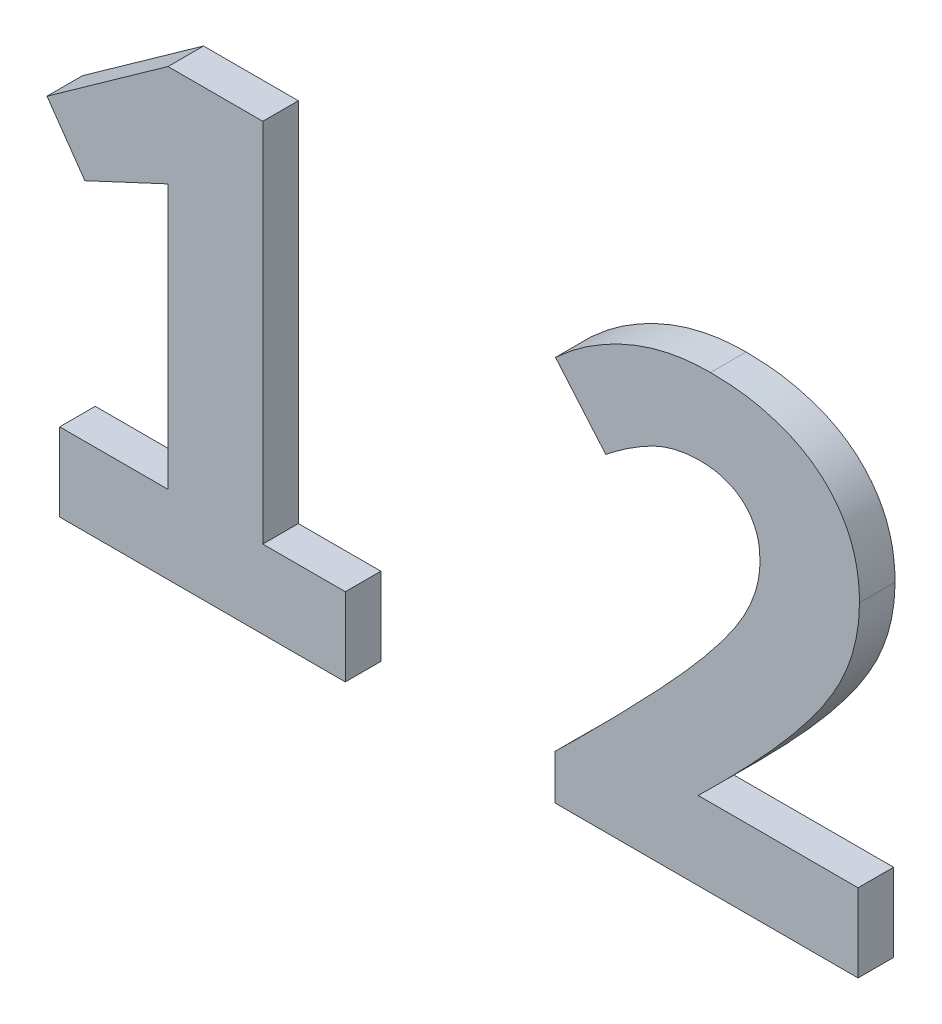
SolidWorks part; units mm, degrees
ref_plane "Front Plane" through (0, 0, 0) normal (0, 0, 1) x (1, 0, 0)
ref_plane "Top Plane" through (0, 0, 0) normal (0, 1, 0) x (1, 0, 0)
ref_plane "Right Plane" through (0, 0, 0) normal (1, 0, 0) x (0, 0, -1)
sketch "Sketch1" plane through (0, 0, 0) normal (0, 0, 1) x (1, 0, 0)
  text T0 "<b>1 2</b>" font "Dubai" height 25
extrude "Boss-Extrude1" add sketch "Sketch1" along normal blind 2
